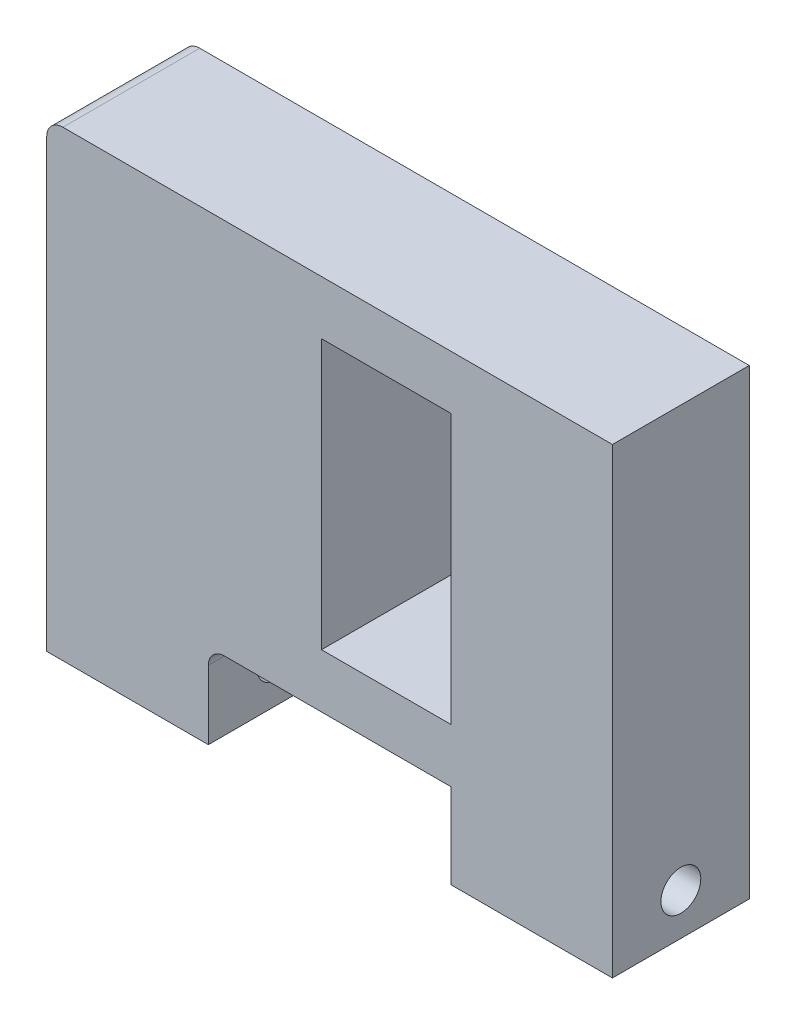
SolidWorks part; units mm, degrees
ref_plane "Front Plane" through (0, 0, 0) normal (0, 0, 1) x (1, 0, 0)
ref_plane "Top Plane" through (0, 0, 0) normal (0, 1, 0) x (1, 0, 0)
ref_plane "Right Plane" through (0, 0, 0) normal (1, 0, 0) x (0, 0, -1)
sketch "Sketch1" plane through (0, 0, 0) normal (0, 0, 1) x (1, 0, 0)
  line L0 (11.25, -11.44) -> (26.25, -11.44)
  line L1 (-11.25, -3.56) -> (11.25, -3.56)
  line L2 (-11.25, -3.56) -> (-11.25, -11.44)
  line L4 (11.25, -3.56) -> (11.25, -11.44)
  line L5 (-26.25, 31.44) -> (26.25, 31.44)
  line L6 (-26.25, 31.44) -> (-26.25, -11.44)
  line L7 (-26.25, -11.44) -> (-11.25, -11.44)
  line L8 (26.25, 31.44) -> (26.25, -11.44)
  dimension "D1" = 22.5
  dimension "D2" = 15
  dimension "D3" = 11.25
  dimension "D4" = 15
  dimension "D5" = 35
  dimension "D6" = 7.88
  dimension "D7" = 31.44
extrude "Boss-Extrude1" add sketch "Sketch1" along normal blind 12.7
fillet "Fillet1" radius 1.5 1 edges at (-26.25, 31.44, 6.35)
fillet "Fillet2" radius 1.5 1 edges at (-11.25, -3.56, 6.35)
sketch "Sketch4" plane through (-26.25, 0, 0) normal (-1, 0, 0) x (0, 0, 1)
  line L2 (0, 29.94) -> (0, -11.44) construction
  line L3 (12.7, -11.44) -> (0, -11.44) construction
  circle A2 centre (6.35, -7.56) radius 1.85
  dimension "D1" = 6.35
  dimension "D2" = 3.7
  dimension "D3" = 3.88
extrude "Cut-Extrude1" cut sketch "Sketch4" against normal through all
sketch "Sketch11" plane through (0, 0, 12.7) normal (0, 0, 1) x (1, 0, 0)
  line L1 (-0.75, 26.445) -> (11.25, 26.445)
  line L2 (-0.75, 26.445) -> (-0.75, 1.445)
  line L3 (-0.75, 1.445) -> (11.25, 1.445)
  line L4 (11.25, 26.445) -> (11.25, 1.445)
  line L6 (26.25, -11.44) -> (26.25, 31.44) construction
  line L8 (26.25, 31.44) -> (-24.75, 31.44) construction
  dimension "D1" = 25
  dimension "D2" = 12
  dimension "D3" = 15
  dimension "D4" = 4.995
extrude "Cut-Extrude2" cut sketch "Sketch11" against normal up to surface (12.7 mm away) up to face at (-3.5121, 3.5501, 0)
